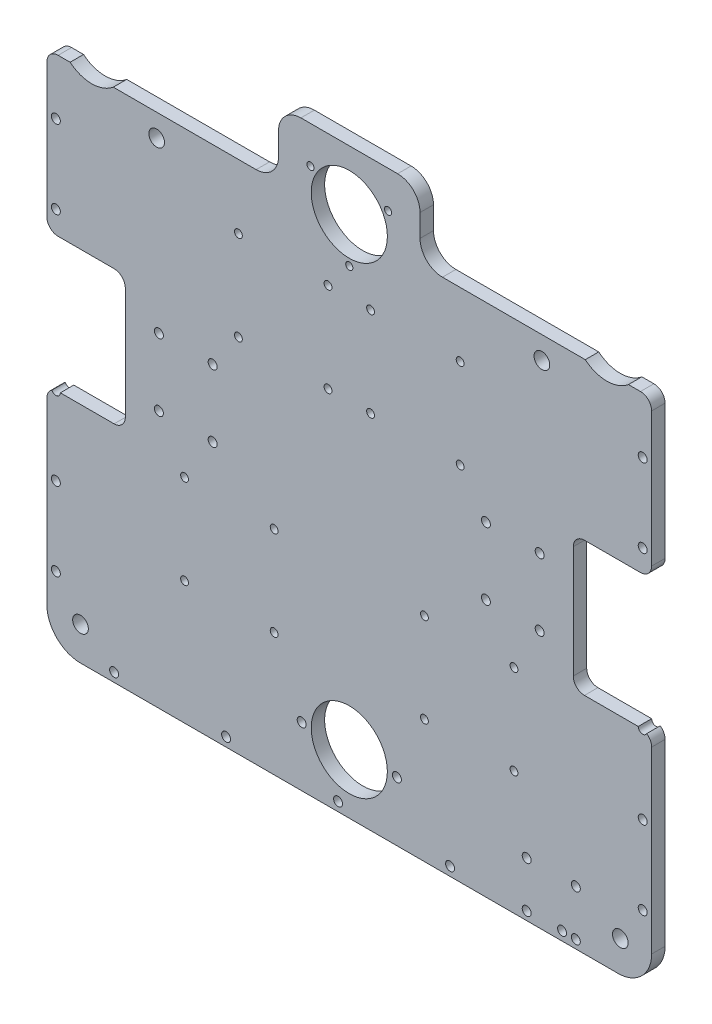
SolidWorks part; units mm, degrees
material "Alumina"
ref_plane "Front Plane" through (0, 0, 0) normal (0, 0, 1) x (1, 0, 0)
ref_plane "Top Plane" through (0, 0, 0) normal (0, 1, 0) x (1, 0, 0)
ref_plane "Right Plane" through (0, 0, 0) normal (1, 0, 0) x (0, 0, -1)
sketch "Sketch1" plane through (0, 0, 0) normal (0, 0, 1) x (1, 0, 0)
  line L1 (-135, 130) -> (135, 130)
  line L2 (-135, 130) -> (-135, -130)
  line L3 (-135, -130) -> (135, -130)
  line L4 (135, 130) -> (135, -130)
  line L5 (-135, 130) -> (135, -130) construction
  line L6 (-135, -130) -> (135, 130) construction
  point P0 (0, 0)
  dimension "D1" = 270
  dimension "D2" = 260
extrude "Boss-Extrude1" add sketch "Sketch1" along normal blind 6
sketch "Sketch2" plane through (0, 0, 6) normal (0, 0, 1) x (1, 0, 0)
  line L0 (-135, 130) -> (-135, -130) construction
  line L1 (-135, 30) -> (-100, 30)
  line L2 (-135, 30) -> (-135, -30)
  line L3 (-135, -30) -> (-100, -30)
  line L4 (-100, 30) -> (-100, -30)
  line L5 (-135, 30) -> (-100, -30) construction
  line L6 (-135, -30) -> (-100, 30) construction
  circle A0 centre (-85, 15) radius 2
  circle A1 centre (-61, 15) radius 2
  circle A2 centre (-61, -15) radius 2
  circle A3 centre (-85, -15) radius 2
  point P0 (-117.5, 0)
  dimension "D3" = 4
  dimension "D4" = 24
  dimension "D5" = 30
  dimension "D6" = 50
  dimension "D1" = 35
  dimension "D2" = 60
extrude "Cut-Extrude1" cut sketch "Sketch2" against normal through all
sketch "Sketch3" plane through (0, 0, 6) normal (0, 0, 1) x (1, 0, 0)
  line L1 (0, -103.5) -> (0, -83.5) construction
  line L2 (0, -103.5) -> (17.3205, -113.5) construction
  line L3 (0, -103.5) -> (-17.3205, -113.5) construction
  circle A3 centre (0, -103.5) radius 17
  dimension "D2" = 34
  dimension "D4" = 120
  dimension "D5" = 120
  dimension "D6" = 20
extrude "Cut-Extrude2" cut sketch "Sketch3" against normal through all
mirror "Mirror1" about plane through (0, 0, 0) normal (1, 0, 0) of "Cut-Extrude1"
mirror "Mirror2" about plane through (0, 0, 0) normal (0, 1, 0) of "Cut-Extrude2"
sketch "Sketch4" plane through (0, 0, 6) normal (0, 0, 1) x (1, 0, 0)
  circle A0 centre (21.25, -103.5) radius 2
  circle A1 centre (-21.25, -103.5) radius 2
  dimension "D1" = 4
extrude "Cut-Extrude3" cut sketch "Sketch4" against normal through all
sketch "Sketch5" plane through (0, 0, 6) normal (0, 0, 1) x (1, 0, 0)
  circle A0 centre (79.2065, -126.2348) radius 2
  circle A1 centre (79.2065, -105.7652) radius 2
  circle A2 centre (101.1382, -105.7652) radius 2
  circle A3 centre (101.1382, -126.2348) radius 2
  dimension "D1" = 4
extrude "Cut-Extrude4" cut sketch "Sketch5" against normal through all
fillet "Fillet1" radius 15 4 edges at (135, 130, 3) (-135, 130, 3) (-135, -130, 3) (135, -130, 3)
sketch "Sketch6" plane through (0, 0, 6) normal (0, 0, 1) x (1, 0, 0)
  circle A0 centre (-115, 115) radius 12.5
  dimension "D1" = 25
extrude "Cut-Extrude5" cut sketch "Sketch6" against normal through all
sketch "Sketch7" plane through (0, 0, 6) normal (0, 0, 1) x (1, 0, 0)
  line L3 (-95.6553, 110.7637) -> (-27.9414, 110.7637)
  line L4 (-27.9414, 110.7637) -> (-27.9414, 130)
  line L5 (120, 130) -> (-120, 130) construction
sketch "Sketch8" plane through (0, 0, 6) normal (0, 0, 1) x (1, 0, 0)
  circle A0 centre (49.5, 31.3) radius 1.75
  circle A1 centre (9.5, 31.3) radius 1.75
  circle A2 centre (9.5, 71.3) radius 1.75
  circle A3 centre (49.5, 71.3) radius 1.75
  circle A4 centre (-49.5, 31.3) radius 1.75
  circle A5 centre (-9.5, 31.3) radius 1.75
  circle A6 centre (-49.5, 71.3) radius 1.75
  circle A7 centre (-9.5, 71.3) radius 1.75
  dimension "D1" = 3.5
extrude "Cut-Extrude6" cut sketch "Sketch8" against normal through all
sketch "Sketch9" plane through (0, 0, 6) normal (0, 0, 1) x (1, 0, 0)
  circle A0 centre (115, 111.5) radius 12.5
  dimension "D1" = 25
extrude "Cut-Extrude7" cut sketch "Sketch9" against normal through all
sketch "Sketch10" plane through (0, 0, 6) normal (0, 0, 1) x (1, 0, 0)
  line L0 (135, 30) -> (135, 115) construction
  line L1 (135, 100) -> (31.5934, 100)
  line L2 (135, 100) -> (135, 130)
  line L3 (135, 130) -> (31.5934, 130)
  line L4 (31.5934, 100) -> (31.5934, 130)
  line L5 (120, 130) -> (-120, 130) construction
  dimension "D1" = 30
extrude "Cut-Extrude8" cut sketch "Sketch10" against normal through all
ref_plane "Plane1" through (0, 0, 0) normal (-1, 0, 0) x (0, 0, 1)
fillet "Fillet2" radius 10 2 edges at (31.5934, 130, 3) (31.5934, 100, 3)
mirror "Mirror3" about plane through (0, 0, 0) normal (-1, 0, 0) of "Cut-Extrude8", "Fillet2"
sketch "Sketch11" plane through (0, 0, 6) normal (0, 0, 1) x (1, 0, 0)
  circle A0 centre (-17.3205, 113.5) radius 1.6
  circle A1 centre (17.3205, 113.5) radius 1.6
  circle A2 centre (0, 83.5) radius 1.6
  circle A3 centre (86, 90) radius 3.5
  circle A4 centre (-86, 90) radius 3.5
  circle A5 centre (121, -116) radius 3.5
  circle A6 centre (-120, -115) radius 3.5
  dimension "D1" = 3.2
  dimension "D2" = 7
extrude "Cut-Extrude9" cut sketch "Sketch11" against normal through all
sketch "Sketch12" plane through (0, 0, 6) normal (0, 0, 1) x (1, 0, 0)
  circle A0 centre (115, 111.5) radius 15
  circle A1 centre (-115, 111.5) radius 15
  dimension "D1" = 30
  dimension "D2" = 30
extrude "Cut-Extrude10" cut sketch "Sketch12" against normal through all
fillet "Fillet3" radius 5 2 edges at (135, 100, 3) (-135, 100, 3)
fillet "Fillet4" radius 5 8 edges at (135, 30, 3) (100, 30, 3) (100, -30, 3) (135, -30, 3) (-135, -30, 3) (-100, -30, 3) (-100, 30, 3) (-135, 30, 3)
sketch "Sketch13" plane through (0, 0, 6) normal (0, 0, 1) x (1, 0, 0)
  line L0 (0, 3.3) -> (0, -3.3) construction
  line L1 (-120, -130) -> (120, -130) construction
  line L2 (-135, -35) -> (-135, -115) construction
  circle A0 centre (33.5446, -34.9403) radius 1.75
  circle A1 centre (73.5446, -34.9403) radius 1.75
  circle A2 centre (73.5446, -74.9403) radius 1.75
  circle A3 centre (33.5446, -74.9403) radius 1.75
  circle A4 centre (-33.5446, -74.9403) radius 1.75
  circle A5 centre (-73.5446, -74.9403) radius 1.75
  circle A6 centre (-73.5446, -34.9403) radius 1.75
  circle A7 centre (-33.5446, -34.9403) radius 1.75
  circle A8 centre (-131, -100) radius 2
  circle A9 centre (-131, -65) radius 2
  circle A10 centre (-131, -30) radius 2
  circle A11 centre (-131, 5) radius 2
  circle A12 centre (-131, 40) radius 2
  circle A13 centre (-131, 75) radius 2
  circle A14 centre (-105, -126) radius 2
  circle A15 centre (-55, -126) radius 2
  circle A16 centre (-5, -126) radius 2
  circle A17 centre (45, -126) radius 2
  circle A18 centre (95, -126) radius 2
  circle A19 centre (145, -126) radius 2
  circle A20 centre (195, -126) radius 2
  circle A21 centre (245, -126) radius 2
  circle A22 centre (295, -126) radius 2
  circle A23 centre (345, -126) radius 2
  circle A24 centre (395, -126) radius 2
  circle A25 centre (445, -126) radius 2
  circle A26 centre (495, -126) radius 2
  circle A28 centre (131, 75) radius 2
  circle A29 centre (131, 40) radius 2
  circle A30 centre (131, 5) radius 2
  circle A31 centre (131, -30) radius 2
  circle A32 centre (131, -65) radius 2
  circle A33 centre (131, -100) radius 2
  dimension "D1" = 3.5
  dimension "D5" = 30
  dimension "D6" = 4
  dimension "D9" = 4
  dimension "D2" = 40
  dimension "D3" = 40
  dimension "D4" = 40
  dimension "D7" = 4
  dimension "D10" = 4
  dimension "D11" = 30
  dimension "D8" = 6
  dimension "D12" = 13
extrude "Cut-Extrude11" cut sketch "Sketch13" against normal through all
